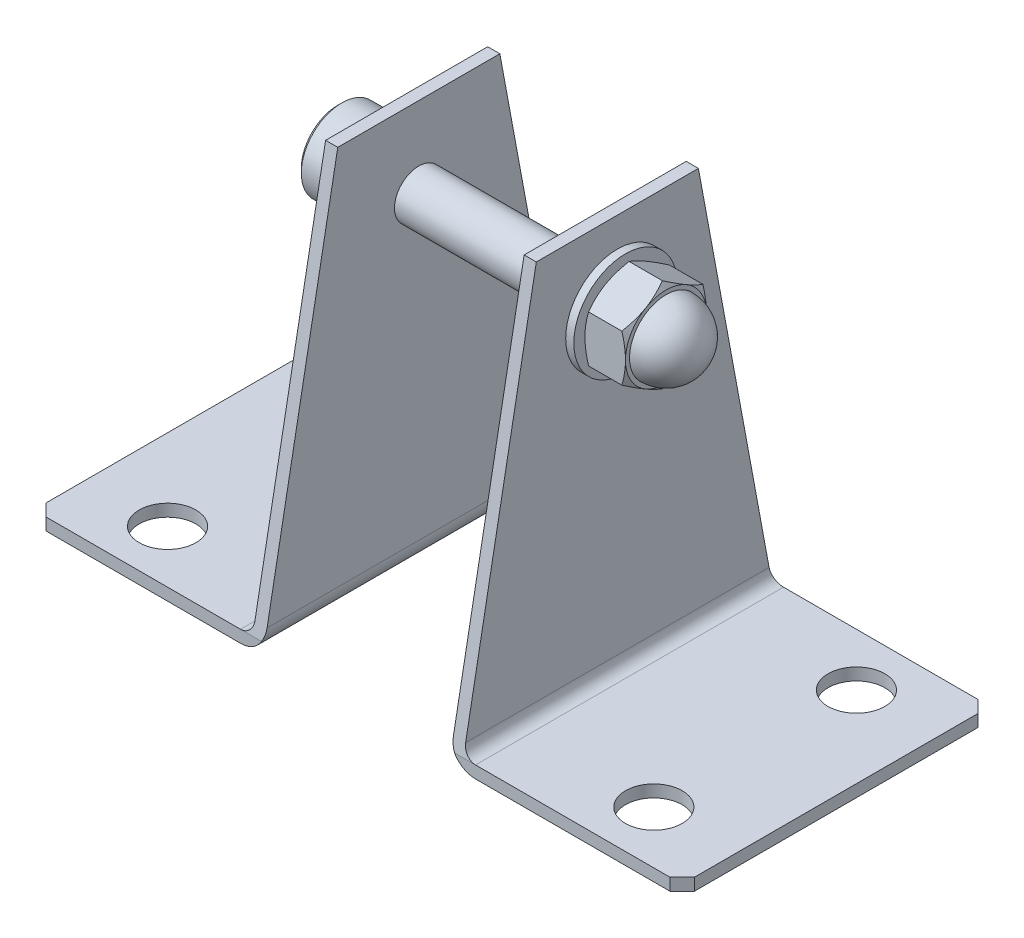
SolidWorks part; units mm, degrees
ref_plane "Front Plane" through (0, 0, 0) normal (0, 0, 1) x (1, 0, 0)
ref_plane "Top Plane" through (0, 0, 0) normal (0, 1, 0) x (1, 0, 0)
ref_plane "Right Plane" through (0, 0, 0) normal (1, 0, 0) x (0, 0, -1)
sketch "Sketch1" plane through (0, 0, 0) normal (0, 0, 1) x (1, 0, 0)
  line L0 (-40, 0) -> (-14.5, 0)
  line L1 (-11.5, 3) -> (-11.5, 50)
  line L2 (-40, 1.5) -> (-14.5, 1.5)
  line L3 (-13, 3) -> (-13, 50)
  line L4 (-40, 1.5) -> (-40, 0)
  line L5 (-13, 50) -> (-11.5, 50)
  line L6 (0, 0) -> (0, 50) construction
  line L7 (13, 50) -> (11.5, 50)
  line L8 (40, 1.5) -> (40, 0)
  line L9 (13, 3) -> (13, 50)
  line L10 (40, 1.5) -> (14.5, 1.5)
  line L11 (11.5, 3) -> (11.5, 50)
  line L12 (40, 0) -> (14.5, 0)
  arc A0 (-14.5, 0) -> (-11.5, 3) centre (-14.5, 3) ccw
  arc A1 (-14.5, 1.5) -> (-13, 3) centre (-14.5, 3) ccw
  arc A2 (14.5, 1.5) -> (13, 3) centre (14.5, 3) cw
  arc A3 (14.5, 0) -> (11.5, 3) centre (14.5, 3) cw
  dimension "FIX_2" = 3
  dimension "FIX_1" = 50
  dimension "FIX_4" = 23
  dimension "FIX_5" = 80
  dimension "FIX_3" = 1.5
extrude "Boss-Extrude1" add sketch "Sketch1" along normal mid plane 38
sketch "Sketch2" plane through (0, 0, 0) normal (1, 0, 0) x (0, 0, -1)
  line L0 (-19, 50) -> (-10, 50)
  line L1 (-10, 50) -> (-19, 1.5)
  line L2 (-19, 1.5) -> (-19, 50)
  line L3 (10, 50) -> (19, 50)
  line L4 (19, 50) -> (19, 1.5)
  line L5 (19, 1.5) -> (10, 50)
  line L6 (0, 50) -> (0, 0) construction
  dimension "FIX_7" = 9
  dimension "FIX_8" = 48.5
  dimension "FIX_9" = 38
extrude "Cut-Extrude1" cut sketch "Sketch2" against normal through all and the other way through all
sketch "Sketch3" plane through (13, 0, 0) normal (1, 0, 0) x (0, 0, -1)
  circle A0 centre (0, 40) radius 3
  dimension "FIX_10" = 6
  dimension "FIX_11" = 40
extrude "Cut-Extrude2" cut sketch "Sketch3" against normal through all
sketch "Sketch4" plane through (0, 1.5, 0) normal (0, 1, 0) x (1, 0, 0)
  line L0 (-30, 12.5) -> (30, 12.5) construction
  line L1 (30, 12.5) -> (30, -12.5) construction
  line L2 (30, -12.5) -> (-30, -12.5) construction
  line L3 (-30, -12.5) -> (-30, 12.5) construction
  circle A0 centre (-30, 12.5) radius 3.5
  circle A1 centre (-30, -12.5) radius 3.5
  circle A2 centre (30, 12.5) radius 3.5
  circle A3 centre (30, -12.5) radius 3.5
  point P6 (0, 12.5)
  point P8 (-30, 0)
  dimension "FIX_12" = 7
  dimension "FIX_13" = 25
  dimension "FIX_14" = 60
extrude "Cut-Extrude3" cut sketch "Sketch4" against normal through all
chamfer "Chamfer1" distance 1.5 2 edges at (-40, 0.75, -19) (-40, 0.75, 19)
chamfer "Chamfer2" distance 1.5 2 edges at (40, 0.75, -19) (40, 0.75, 19)
sketch "Sketch5" plane through (0, 0, 0) normal (0, 0, 1) x (1, 0, 0)
  line L0 (-14, 40) -> (14, 40) construction
  line L2 (-14, 46.375) -> (-13, 46.375)
  line L3 (-14, 46.375) -> (-14, 43)
  line L4 (-14, 43) -> (-13, 43)
  line L5 (-13, 46.375) -> (-13, 43)
  line L6 (13, 46.375) -> (14, 46.375)
  line L7 (13, 46.375) -> (13, 43)
  line L8 (13, 43) -> (14, 43)
  line L9 (14, 46.375) -> (14, 43)
  dimension "FIX_19" = 40
  dimension "FIX_42" = 12.75
  dimension "FIX_23" = 1
  dimension "FIX_43" = 6
revolve "Revolve1" add sketch "Sketch5" angle 360 about L0
sketch "Sketch6" plane through (0, 0, 0) normal (0, 0, 1) x (1, 0, 0)
  line L0 (-21.5, 40) -> (23.5, 40) construction
  line L1 (-21.5, 40) -> (23.5, 40)
  line L2 (-21.5, 40) -> (-21.5, 45)
  line L3 (-21.5, 45) -> (-15.5, 45)
  line L4 (-15.5, 45) -> (-15.5, 46.1)
  line L5 (-15.5, 46.1) -> (-14, 46.1)
  line L6 (-14, 46.1) -> (-14, 43)
  line L7 (-14, 46.375) -> (-14, 43) construction
  line L9 (-14, 43) -> (14, 43)
  line L12 (14, 43) -> (14, 45)
  line L14 (14, 45) -> (19, 45)
  line L15 (19, 45) -> (19, 44.5)
  arc A0 (19, 44.5) -> (23.5, 40) centre (19, 40) cw
  dimension "FIX_18" = 4.5
  dimension "FIX_17" = 40
  dimension "FIX_22" = 6
  dimension "FIX_24" = 12.2
  dimension "FIX_20" = 1.5
  dimension "FIX_25" = 10
  dimension "FIX_21" = 6
  dimension "FIX_27" = 10
  dimension "FIX_26" = 5
revolve "Revolve2" add sketch "Sketch6" angle 360 about L0
sketch "Sketch7" plane through (14, 0, 0) normal (1, 0, 0) x (0, 0, -1)
  line L1 (0, 34.2265) -> (5, 37.1132)
  line L2 (5, 37.1132) -> (5, 42.8868)
  line L3 (5, 42.8868) -> (0, 45.7735)
  line L4 (0, 45.7735) -> (-5, 42.8868)
  line L5 (-5, 42.8868) -> (-5, 37.1132)
  line L6 (-5, 37.1132) -> (0, 34.2265)
  circle A0 centre (0, 40) radius 5 construction
  dimension "FIX_29" = 40
  dimension "FIX_30" = 10
extrude "Boss-Extrude2" add sketch "Sketch7" along normal blind 5
sketch "Sketch8" plane through (0, 0, 0) normal (0, 0, 1) x (1, 0, 0)
  line L0 (18.5534, 45.7735) -> (19, 45.7735)
  line L1 (19, 45.7735) -> (19, 45)
  line L2 (19, 45) -> (18.5534, 45.7735)
  line L3 (14.4466, 45.7735) -> (14, 45.7735)
  line L4 (14, 45.7735) -> (14, 45)
  line L5 (14, 45) -> (14.4466, 45.7735)
  line L6 (-21.5, 40) -> (19, 40) construction
  line L7 (19, 45) -> (19, 44.5) construction
  line L9 (-21.5, 40) -> (-21.5, 45) construction
  line L10 (-21.5, 40) -> (-17.0566, 40)
  line L11 (-21.5, 40) -> (-21.5, 42.5)
  line L12 (-21.5, 42.5) -> (-18.5, 42.5)
  line L13 (-17.0566, 40) -> (-18.5, 42.5)
  dimension "FIX_32" = 40
  dimension "FIX_36" = 10
  dimension "FIX_33" = 30
  dimension "FIX_34" = 60
  dimension "FIX_37" = 5
  dimension "FIX_35" = 3
revolve "Cut-Revolve1" cut sketch "Sketch8" angle 360 about L6
sketch "Sketch9" plane through (-21.5, 0, 0) normal (-1, 0, 0) x (0, 0, 1)
  line L1 (2.8868, 40) -> (1.4434, 42.5)
  line L2 (1.4434, 42.5) -> (-1.4434, 42.5)
  line L3 (-1.4434, 42.5) -> (-2.8868, 40)
  line L4 (-2.8868, 40) -> (-1.4434, 37.5)
  line L5 (-1.4434, 37.5) -> (1.4434, 37.5)
  line L6 (1.4434, 37.5) -> (2.8868, 40)
  circle A0 centre (0, 40) radius 2.5 construction
  dimension "FIX_39" = 5
extrude "Cut-Extrude4" cut sketch "Sketch9" against normal blind 3
chamfer "Chamfer3" distance 0.5 1 edges at (-21.5, 35, 0)
